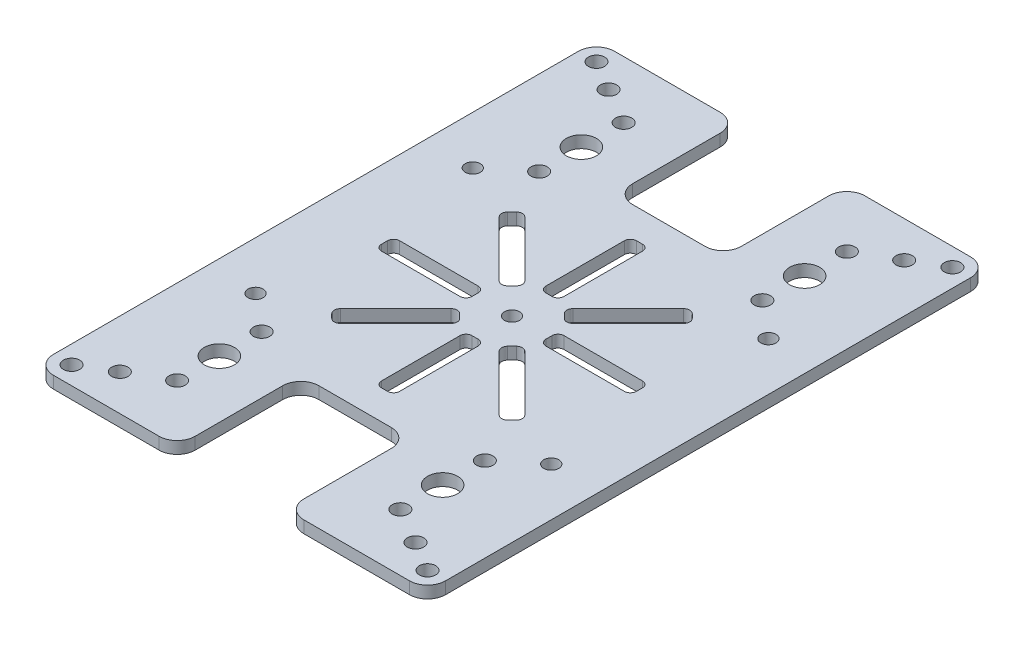
SolidWorks part; units mm, degrees
ref_plane "Front Plane" through (0, 0, 0) normal (0, 0, 1) x (1, 0, 0)
ref_plane "Top Plane" through (0, 0, 0) normal (0, 1, 0) x (1, 0, 0)
ref_plane "Right Plane" through (0, 0, 0) normal (1, 0, 0) x (0, 0, -1)
sketch "Sketch1" plane through (0, 0, 0) normal (0, 1, 0) x (1, 0, 0)
  line L0 (0, 46.9794) -> (0, -46.0206) construction
  line L1 (9, 26) -> (-9, 26)
  line L2 (-9, 26) -> (-9, 46.5)
  line L3 (-9, 46.5) -> (-32.5, 46.5)
  line L4 (-32.5, 46.5) -> (-32.5, -46.5)
  line L5 (-81.4948, 0) -> (81.4948, 0) construction
  line L6 (-9, -46.5) -> (-32.5, -46.5)
  line L7 (-9, -26) -> (-9, -46.5)
  line L8 (9, -26) -> (-9, -26)
  line L9 (9, -26) -> (9, -46.5)
  line L10 (9, -46.5) -> (32.5, -46.5)
  line L11 (32.5, 46.5) -> (32.5, -46.5)
  line L12 (9, 46.5) -> (32.5, 46.5)
  line L13 (9, 26) -> (9, 46.5)
  point P3 (32.5, 0)
  point P16 (-32.5, 0)
  point P20 (0, -26)
  point P25 (0, 26)
  dimension "D1" = 93
  dimension "D2" = 32.5
  dimension "D3" = 23.5
  dimension "D4" = 26
  dimension "D5" = 46.5
extrude "Boss-Extrude1" add sketch "Sketch1" along normal blind 2
fillet "Fillet1" radius 3 12 edges at (-32.5, 1, -46.5) (-32.5, 1, 46.5) (-9, 1, 46.5) (-9, 1, 26) (9, 1, 26) (9, 1, 46.5) (32.5, 1, 46.5) (32.5, 1, -46.5) (9, 1, -46.5) (-9, 1, -46.5) (9, 1, -26) (-9, 1, -26)
sketch "Sketch2" plane through (0, 2, 0) normal (0, 1, 0) x (1, 0, 0)
  line L0 (0, 26) -> (0, -26) construction
  line L1 (6, 26) -> (-6, 26) construction
  line L2 (-6, -26) -> (6, -26) construction
  line L4 (0.5, 21.125) -> (-0.5, 21.125)
  line L5 (1.5, 20.125) -> (1.5, 7.125)
  line L6 (0.5, 6.125) -> (-0.5, 6.125)
  line L7 (-1.5, 20.125) -> (-1.5, 7.125)
  line L8 (1.5, 21.125) -> (-1.5, 6.125) construction
  line L9 (1.5, 6.125) -> (-1.5, 21.125) construction
  circle A0 centre (0, 0) radius 1.25
  arc A1 (-0.5, 6.125) -> (-1.5, 7.125) centre (-0.5, 7.125) cw
  arc A2 (1.5, 7.125) -> (0.5, 6.125) centre (0.5, 7.125) cw
  arc A3 (0.5, 21.125) -> (1.5, 20.125) centre (0.5, 20.125) cw
  arc A4 (-0.5, 21.125) -> (-1.5, 20.125) centre (-0.5, 20.125) ccw
  point P9 (0, 13.625)
  dimension "D1" = 2.5
  dimension "D5" = 1
  dimension "D2" = 3
  dimension "D3" = 15
  dimension "D4" = 6.125
extrude "Cut-Extrude1" cut sketch "Sketch2" against normal up to next
pattern_circular "CirPattern1" count 8 over 360 about axis through (0, 0, 0) along (0, 1, 0) of "Cut-Extrude1"
sketch "Sketch3" plane through (0, 2, 0) normal (0, 1, 0) x (1, 0, 0)
  line L0 (-12, 46.5) -> (-29.5, 46.5) construction
  line L1 (-32.5, 43.5) -> (-32.5, -43.5) construction
  line L2 (-24.5, 40.5) -> (-24.5, 18) construction
  line L3 (-18.5, 37) -> (-18.5, 23) construction
  circle A0 centre (-29.5, 43.5) radius 1.35
  circle A1 centre (-24.5, 40.5) radius 1.35
  circle A2 centre (-24.5, 18) radius 1.25
  circle A3 centre (-18.5, 37) radius 1.35
  circle A4 centre (-18.5, 23) radius 1.35
  circle A5 centre (-18.5, 30) radius 2.5
  dimension "D2" = 3
  dimension "D3" = 2.7
  dimension "D4" = 2.7
  dimension "D5" = 3
  dimension "D6" = 5
  dimension "D7" = 2.5
  dimension "D9" = 2.7
  dimension "D10" = 2.7
  dimension "D11" = 5
  dimension "D1" = 3
  dimension "D8" = 22.5
  dimension "D12" = 14
  dimension "D13" = 9.5
  dimension "D14" = 14
extrude "Cut-Extrude2" cut sketch "Sketch3" against normal up to next
mirror "Mirror1" about plane through (0, 0, 0) normal (1, 0, 0) of "Cut-Extrude2" second plane through (0, 0, 0) second plane normal (0, 0, 1)
